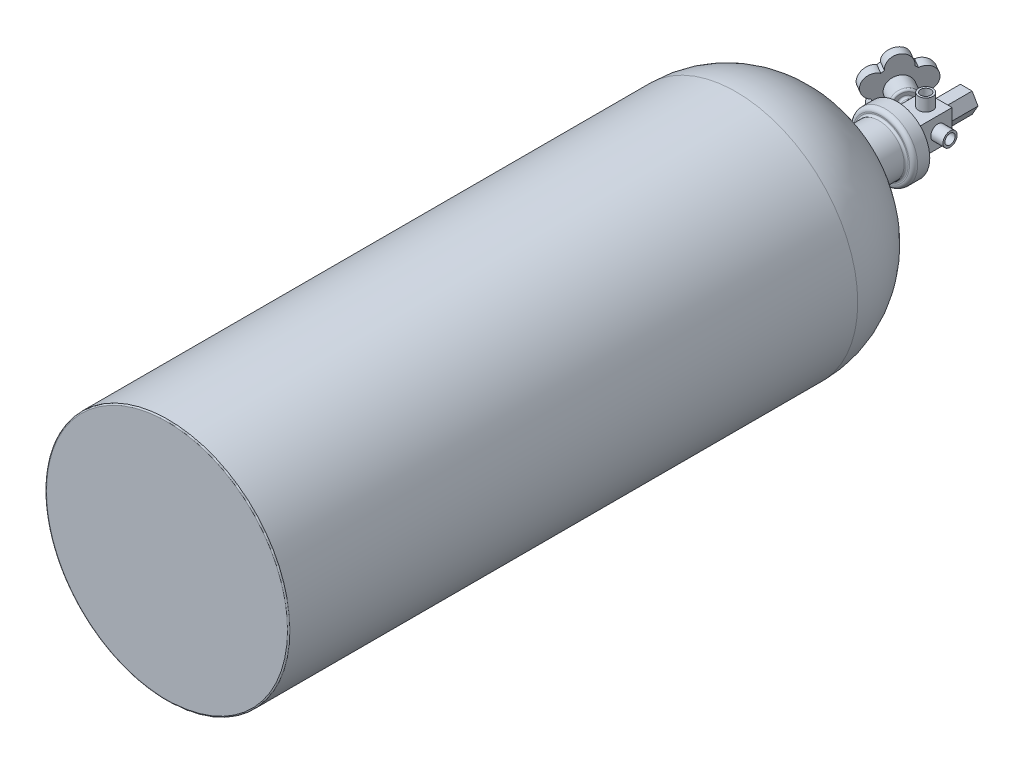
SolidWorks part; units mm, degrees
material "1345 Alloy"
ref_plane "Front Plane" through (0, 0, 0) normal (0, 0, 1) x (1, 0, 0)
ref_plane "Top Plane" through (0, 0, 0) normal (0, 1, 0) x (1, 0, 0)
ref_plane "Right Plane" through (0, 0, 0) normal (1, 0, 0) x (0, 0, -1)
sketch "Sketch3" plane through (0, 0, 0) normal (0, 1, 0) x (1, 0, 0)
  line L0 (0, 0) -> (-75.438, 0)
  line L1 (-76.2, 0.762) -> (-76.2, 356.2351)
  line L3 (-15.748, 425.45) -> (-15.748, 445.77)
  line L4 (-17.018, 447.04) -> (-17.78, 447.04)
  line L5 (-20.32, 449.58) -> (-20.32, 457.2)
  line L6 (-20.32, 457.2) -> (0, 457.2)
  line L7 (0, 0) -> (0, 182.7971) construction
  line L8 (0, 0) -> (0, 457.2)
  arc A0 (-76.2, 356.2351) -> (-21.2436, 419.1577) centre (-12.7, 356.2351) cw
  arc A1 (-75.438, 0) -> (-76.2, 0.762) centre (-75.438, 0.762) cw
  arc A2 (-21.2436, 419.1577) -> (-15.748, 425.45) centre (-22.098, 425.45) ccw
  arc A3 (-15.748, 445.77) -> (-17.018, 447.04) centre (-17.018, 445.77) ccw
  arc A4 (-17.78, 447.04) -> (-20.32, 449.58) centre (-17.78, 449.58) cw
  dimension "D1" = 63.5
  dimension "D2" = 0.762
  dimension "D3" = 2.54
  dimension "D4" = 1.27
  dimension "D7" = 6.35
  dimension "D5" = 457.2
  dimension "D6" = 152.4
  dimension "D8" = 20.32
  dimension "D9" = 20.32
  dimension "D10" = 0.762
  dimension "D11" = 7.62
revolve "Revolve1" add sketch "Sketch3" angle 360 about L7
sketch "Sketch4" plane through (0, 0, -457.2) normal (0, 0, -1) x (-1, 0, 0)
  line L1 (8.89, 8.89) -> (-8.89, 8.89)
  line L2 (8.89, 8.89) -> (8.89, -8.89)
  line L3 (8.89, -8.89) -> (-8.89, -8.89)
  line L4 (-8.89, 8.89) -> (-8.89, -8.89)
  line L5 (8.89, 8.89) -> (-8.89, -8.89) construction
  line L6 (8.89, -8.89) -> (-8.89, 8.89) construction
  point P0 (0, 0)
  dimension "D1" = 17.78
extrude "Boss-Extrude1" add sketch "Sketch4" along normal blind 25.4
sketch "Sketch5" plane through (0, -8.89, 0) normal (0, -1, 0) x (1, 0, 0)
  line L0 (0, -462.28) -> (0, -457.2) construction
  line L1 (8.89, -457.2) -> (-8.89, -457.2) construction
  circle A0 centre (0, -462.28) radius 3.175
  circle A1 centre (0, -462.28) radius 2.54
  dimension "D1" = 6.35
  dimension "D2" = 5.08
  dimension "D3" = 5.08
extrude "Boss-Extrude2" add sketch "Sketch5" along normal blind 5.08
sketch "Sketch6" plane through (8.89, 0, 0) normal (1, 0, 0) x (0, 0, -1)
  line L0 (473.71, 0) -> (457.2, 0) construction
  line L1 (457.2, 8.89) -> (457.2, -8.89) construction
  circle A0 centre (473.71, 0) radius 4.445
  circle A1 centre (473.71, 0) radius 3.175
  dimension "D1" = 8.89
  dimension "D3" = 6.35
  dimension "D2" = 16.51
extrude "Boss-Extrude3" add sketch "Sketch6" along normal blind 7.62
sketch "Sketch7" plane through (0, 8.89, 0) normal (0, 1, 0) x (1, 0, 0)
  line L0 (0, 474.98) -> (0, 457.2) construction
  line L1 (-8.89, 457.2) -> (8.89, 457.2) construction
  circle A0 centre (0, 474.98) radius 4.445
  circle A1 centre (0, 474.98) radius 3.175
  dimension "D1" = 8.89
  dimension "D2" = 6.35
  dimension "D3" = 17.78
extrude "Boss-Extrude4" add sketch "Sketch7" along normal blind 7.62
sketch "Sketch8" plane through (-8.89, 0, 0) normal (-1, 0, 0) x (0, 0, 1)
  line L0 (-474.98, -8.89) -> (-474.98, 8.89) construction
  line L1 (-482.6, -8.89) -> (-457.2, -8.89) construction
  line L2 (-482.6, 8.89) -> (-457.2, 8.89) construction
  line L3 (-457.2, -8.89) -> (-457.2, 8.89) construction
  line L4 (-482.6, 0) -> (-457.2, 0) construction
  line L5 (-482.6, -8.89) -> (-482.6, 8.89) construction
  dimension "D1" = 17.78
ref_plane "Plane1" through (203.4499, 0, -352.3855) normal (-0.5, 0, 0.866) x (0, 1, 0)
sketch "Sketch10" plane through (203.4499, 0, -352.3855) normal (-0.5, 0, 0.866) x (0, 1, 0)
  line L0 (3.175, 233.601) -> (3.175, 252.651)
  line L1 (4.445, 253.921) -> (6.35, 253.921)
  line L2 (7.62, 255.191) -> (7.62, 265.351)
  line L3 (7.62, 265.351) -> (0, 265.351)
  line L4 (0, 0) -> (0, 243.3839) construction
  line L5 (3.175, 233.601) -> (0, 233.601)
  line L6 (0, 265.351) -> (0, 233.601)
  line L9 (8.89, 233.601) -> (-8.89, 233.601) construction
  arc A0 (6.35, 253.921) -> (7.62, 255.191) centre (6.35, 255.191) ccw
  arc A1 (3.175, 252.651) -> (4.445, 253.921) centre (4.445, 252.651) cw
  dimension "D1" = 1.27
  dimension "D2" = 6.35
  dimension "D3" = 10.16
  dimension "D4" = 15.24
  dimension "D5" = 19.05
revolve "Revolve2" add sketch "Sketch10" angle 360 about L4
sketch "Sketch14" plane through (-229.8007, 0, -132.6755) normal (-0.866, 0, -0.5) x (-0.5, 0, 0.866)
  line L0 (-406.8997, -8.89) -> (-406.8997, 8.89) construction
  circle A0 centre (-406.8997, 0) radius 13.335
  dimension "D1" = 26.67
extrude "Boss-Extrude5" add sketch "Sketch14" along normal blind 7.62 contours A0
sketch "Sketch11" plane through (-229.8007, 0, -132.6755) normal (-0.866, 0, -0.5) x (-0.5, 0, 0.866)
  line L1 (-406.8997, 19.05) -> (-469.4652, 19.05) construction
  line L2 (-413.4989, 0) -> (-391.5018, 0) construction
  circle A0 centre (-406.8997, 0) radius 13.335 construction
  arc A1 (-413.8847, 11.3592) -> (-399.9147, 11.3592) centre (-406.8997, 12.0326) cw
  arc A2 (-413.8847, 11.3592) -> (-399.9147, 11.3592) centre (-406.8997, 0) cw
  dimension "D2" = 19.05
  dimension "D1" = 13.97
extrude "Boss-Extrude6" add sketch "Sketch11" along normal up to surface (7.62 mm away) contours A1 A2 up to face at (-39.6175, 0, -477.3226)
pattern_circular "CirPattern1" count 5 over 360 about axis through (203.4499, 0, -352.3855) along (0.866, 0, 0.5) of "Boss-Extrude6"
sketch "Sketch15" plane through (203.4499, 0, -352.3855) normal (-0.5, 0, 0.866) x (0, 1, 0)
  line L0 (20.32, 270.431) -> (20.32, 290.751)
  line L1 (20.32, 290.751) -> (0, 290.751)
  line L2 (0, 0) -> (0, 541.3314) construction
  line L3 (8.89, 272.463) -> (8.89, 272.971)
  line L4 (10.7357, 272.971) -> (-3.1329, 272.971) construction
  line L5 (8.89, 272.971) -> (0, 272.971)
  line L6 (0, 290.751) -> (0, 272.971)
  arc A0 (20.32, 270.431) -> (8.89, 272.463) centre (10.2768, 247.1009) ccw
  dimension "D1" = 25.4
  dimension "D2" = 8.89
  dimension "D3" = 20.32
  dimension "D4" = 2.032
  dimension "D5" = 20.32
  dimension "D6" = 5.08
revolve "Cut-Revolve2" cut sketch "Sketch15" angle 360 about L2
sketch "Sketch16" plane through (0, 0, -482.6) normal (0, 0, -1) x (-1, 0, 0)
  line L0 (-3.6662, 6.35) -> (3.6662, 6.35)
  line L1 (-3.6662, -6.35) -> (3.6662, -6.35)
  line L2 (3.6662, -6.35) -> (7.3323, 0)
  line L3 (7.3323, 0) -> (3.6662, 6.35)
  line L4 (-3.6662, 6.35) -> (-7.3323, 0)
  line L5 (-7.3323, 0) -> (-3.6662, -6.35)
  circle A0 centre (0, 0) radius 6.35 construction
  dimension "D1" = 12.7
extrude "Boss-Extrude7" add sketch "Sketch16" along normal blind 17.78
